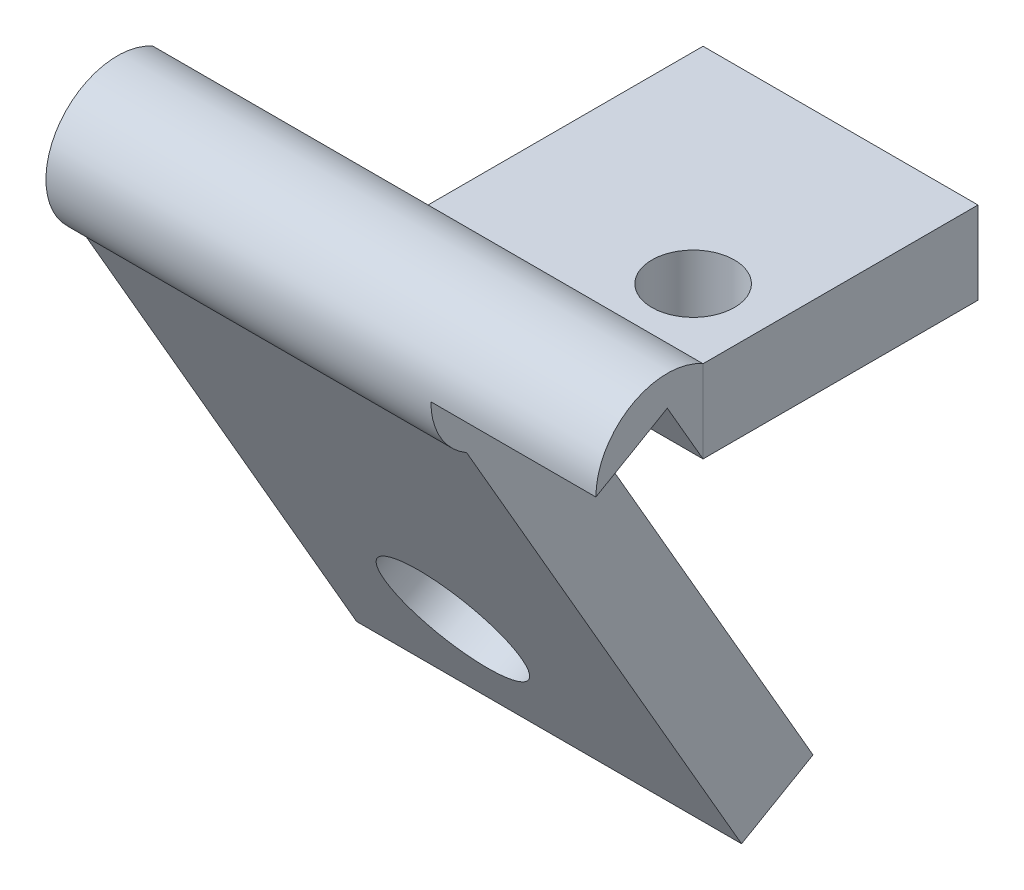
SolidWorks part; units mm, degrees
ref_plane "前基準面" through (0, 0, 0) normal (0, 0, 1) x (1, 0, 0)
ref_plane "上基準面" through (0, 0, 0) normal (0, 1, 0) x (1, 0, 0)
ref_plane "右基準面" through (0, 0, 0) normal (1, 0, 0) x (0, 0, -1)
sketch "草圖1" plane through (0, 0, 0) normal (0, 1, 0) x (1, 0, 0)
  line L2 (-4.36, -7.23) -> (5.64, -7.23)
  line L3 (-4.36, -7.23) -> (-4.36, 2.77)
  line L4 (-4.36, 2.77) -> (5.64, 2.77)
  line L5 (5.64, -7.23) -> (5.64, 2.77)
  line L6 (-4.36, -7.23) -> (5.64, 2.77) construction
  line L7 (-4.36, 2.77) -> (5.64, -7.23) construction
  circle A0 centre (2.94, -4.89) radius 1.5
  point P1 (0.64, -2.23)
  dimension "D1" = 3
  dimension "D2" = 10
  dimension "D3" = 10
extrude "填料-伸長1" add sketch "草圖1" along normal blind 3 contours A0 | L3 L2 L5 L4
sketch "草圖3" plane through (5.64, 0, 0) normal (1, 0, 0) x (0, 0, -1)
  line L0 (-7.23, 0) -> (2.77, -17.3205)
  line L1 (-7.23, 0) -> (2.77, 0) construction
  line L2 (2.77, -17.3205) -> (0.1719, -18.8205)
  line L3 (0.1719, -18.8205) -> (-9.8281, -1.5)
  line L4 (-9.8281, -1.5) -> (-7.23, 0)
  arc A0 (-7.23, 3) -> (-9.8281, -1.5) centre (-8.529, 0.75) ccw
  line M8 (-7.23, 3) -> (-7.23, 0)
  dimension "D1" = 60
  dimension "D2" = 3
  dimension "D3" = 20
extrude "填料-伸長3" add sketch "草圖3" against normal blind 20 separate body contours A0 L4 M8 | L4 L3 L2 L0
sketch "草圖4" plane through (0, -3.1307, 5.4225) normal (0, 0.5, -0.866) x (-1, 0, 0)
  line L1 (14.36, -16.385) -> (-5.64, -16.385) construction
  line L2 (14.36, 3.615) -> (14.36, -16.385) construction
  circle A0 centre (8.36, -11.385) radius 2.5
  dimension "D3" = 5
  dimension "D1" = 5
  dimension "D2" = 6
extrude "除料-伸長1" cut sketch "草圖4" against normal blind 10
sketch "草圖5" plane through (0, -3.1307, 5.4225) normal (0, 0.5, -0.866) x (-1, 0, 0)
  line L0 (14.36, 6.2131) -> (-5.64, 6.2131) construction
  line L1 (-5.64, -16.385) -> (0.36, -16.385)
  line L2 (-5.64, -16.385) -> (-5.64, 6.2131)
  line L3 (-5.64, 6.2131) -> (0.36, 6.2131)
  line L4 (0.36, -16.385) -> (0.36, 6.2131)
  dimension "D1" = 6
extrude "除料-伸長2" cut sketch "草圖5" against normal blind 10
